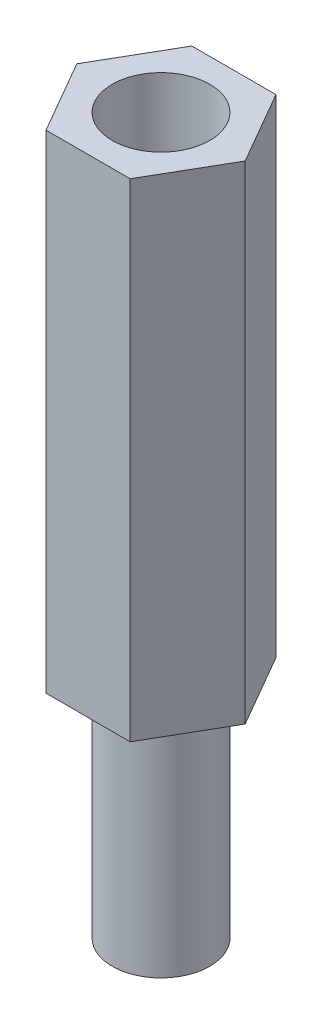
SolidWorks part; units mm, degrees
material "Nylon 6/10"
ref_plane "Front Plane" through (0, 0, 0) normal (0, 0, 1) x (1, 0, 0)
ref_plane "Top Plane" through (0, 0, 0) normal (0, 1, 0) x (1, 0, 0)
ref_plane "Right Plane" through (0, 0, 0) normal (1, 0, 0) x (0, 0, -1)
sketch "Sketch1" plane through (0, 0, 0) normal (0, 1, 0) x (1, 0, 0)
  line L1 (-1.2946, 2.2422) -> (-2.5891, 0)
  line L2 (-2.5891, 0) -> (-1.2946, -2.2422)
  line L3 (-1.2946, -2.2422) -> (1.2946, -2.2422)
  line L4 (1.2946, -2.2422) -> (2.5891, 0)
  line L5 (2.5891, 0) -> (1.2946, 2.2422)
  line L6 (1.2946, 2.2422) -> (-1.2946, 2.2422)
  circle A0 centre (0, 0) radius 1.5
  circle A1 centre (0, 0) radius 2.25 construction
  circle A2 centre (0, 0) radius 2.2422 construction
  dimension "D1" = 3
  dimension "D2" = 4.5
  dimension "D3" = 2.5891
extrude "Boss-Extrude1" add sketch "Sketch1" along normal blind 15
sketch "Sketch2" plane through (0, 0, 0) normal (0, -1, 0) x (1, 0, 0)
  circle A1 centre (0, 0) radius 1.5
  circle A2 centre (0, 0) radius 1.5 construction
  circle A3 centre (0, 0) radius 1.5
extrude "Boss-Extrude3" add sketch "Sketch2" along normal blind 7 separate body contours A1
